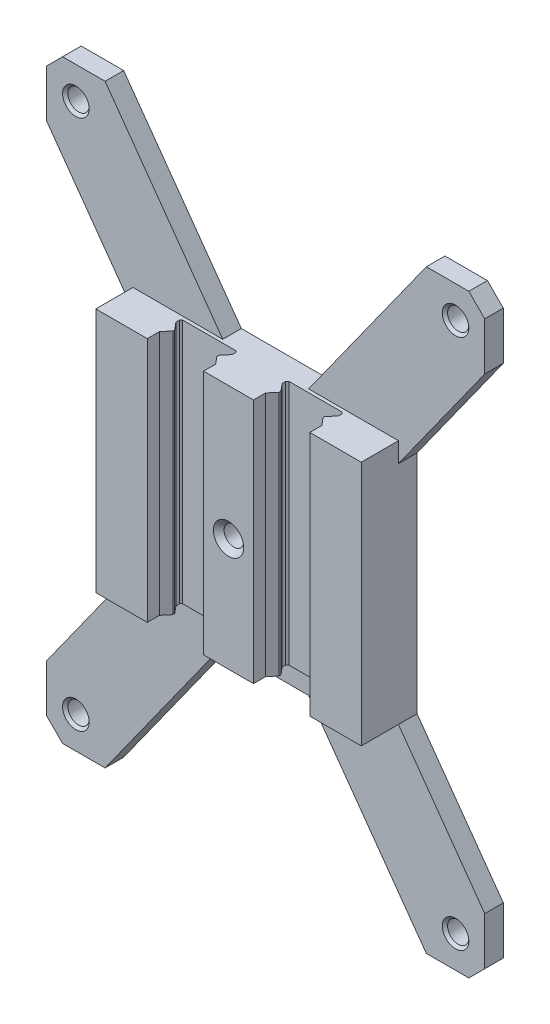
SolidWorks part; units mm, degrees
material "PET"
ref_plane "Přední rovina" through (0, 0, 0) normal (0, 0, 1) x (1, 0, 0)
ref_plane "Horní rovina" through (0, 0, 0) normal (0, 1, 0) x (1, 0, 0)
ref_plane "Pravá rovina" through (0, 0, 0) normal (1, 0, 0) x (0, 0, -1)
sketch "Skica1" plane through (0, 0, 0) normal (0, 0, 1) x (1, 0, 0)
  line L2 (-25, -25) -> (25, -25)
  line L3 (-25, -25) -> (-25, 25)
  line L4 (-25, 25) -> (25, 25)
  line L5 (25, -25) -> (25, 25)
  line L6 (-25, -25) -> (25, 25) construction
  line L7 (-25, 25) -> (25, -25) construction
  point P1 (0, 0)
  dimension "D1" = 50
  dimension "D2" = 50
extrude "Přidat vysunutím1" add sketch "Skica1" along normal blind 10
sketch "Skica3" plane through (0, 25, 0) normal (0, 1, 0) x (1, 0, 0)
  line L0 (-10, 0) -> (-10, -10) construction
  line L1 (25, 0) -> (-25, 0) construction
  line L2 (25, -10) -> (-25, -10) construction
  line L3 (-15, -10) -> (-15, -7.33) construction
  line L4 (-15, -7.33) -> (-13.8337, -5.94) construction
  line L5 (-13.8337, -5.94) -> (-13.8337, -5.39) construction
  line L6 (-13.8337, -5.39) -> (-15, -4) construction
  line L7 (-15, -4) -> (-15, -3.53) construction
  line L8 (-14.8, -3.33) -> (-5.2, -3.33) construction
  line L9 (-5, -10) -> (-5, -7.33) construction
  line L10 (-5, -7.33) -> (-6.1663, -5.94) construction
  line L11 (-6.1663, -5.94) -> (-6.1663, -5.39) construction
  line L12 (-6.1663, -5.39) -> (-5, -4) construction
  line L13 (-5, -4) -> (-5, -3.53) construction
  line L14 (-15, -3.53) -> (-14.8, -3.33) construction
  line L15 (-5.2, -3.33) -> (-5, -3.53) construction
  line L16 (-15.3, -10) -> (-15.3, -7.2208)
  line L17 (-15.3, -7.2208) -> (-14.1337, -5.8308)
  line L18 (-14.1337, -5.8308) -> (-14.1337, -5.4992)
  line L19 (-14.1337, -5.4992) -> (-15.3, -4.1092)
  line L20 (-15.3, -4.1092) -> (-15.3, -3.4305)
  line L21 (-14.9995, -3.13) -> (-5.0005, -3.13)
  line L22 (-15.3, -3.4305) -> (-14.9995, -3.13)
  line L23 (-25, -10) -> (-25, 0) construction
  line L24 (-15.3, -10) -> (-4.7, -10)
  line L25 (-4.7, -3.4305) -> (-5.0005, -3.13)
  line L26 (-4.7, -4.1092) -> (-4.7, -3.4305)
  line L27 (-5.8663, -5.4992) -> (-4.7, -4.1092)
  line L28 (-5.8663, -5.8308) -> (-5.8663, -5.4992)
  line L29 (-4.7, -7.2208) -> (-5.8663, -5.8308)
  line L30 (-4.7, -10) -> (-4.7, -7.2208)
  line L31 (0, 0) -> (0, -10) construction
  line L32 (15.3, -3.4305) -> (14.9995, -3.13)
  line L33 (15.3, -4.1092) -> (15.3, -3.4305)
  line L34 (14.1337, -5.4992) -> (15.3, -4.1092)
  line L35 (14.1337, -5.8308) -> (14.1337, -5.4992)
  line L36 (15.3, -7.2208) -> (14.1337, -5.8308)
  line L37 (15.3, -10) -> (15.3, -7.2208)
  line L38 (15.3, -10) -> (4.7, -10)
  line L39 (4.7, -10) -> (4.7, -7.2208)
  line L40 (4.7, -7.2208) -> (5.8663, -5.8308)
  line L41 (5.8663, -5.8308) -> (5.8663, -5.4992)
  line L42 (5.8663, -5.4992) -> (4.7, -4.1092)
  line L43 (4.7, -4.1092) -> (4.7, -3.4305)
  line L44 (4.7, -3.4305) -> (5.0005, -3.13)
  line L45 (14.9995, -3.13) -> (5.0005, -3.13)
  point P8 (-14.4168, -4.695)
  point P12 (-15, -3.33)
  point P14 (-14.4168, -6.635)
  point P17 (-5.5832, -6.635)
  point P20 (-5.5832, -4.695)
  point P22 (-5, -3.33)
  point P23 (-10, -3.33)
  point P29 (-13.8337, -5.665)
  point P39 (-10, -3.13)
  dimension "D1" = 5
  dimension "D2" = 50
  dimension "D3" = 50
  dimension "D4" = 0.55
  dimension "D5" = 2.67
  dimension "D6" = 3.33
  dimension "D7" = 6.67
  dimension "D8" = 0.3
  dimension "D9" = 0.3
  dimension "D12" = 0.3
  dimension "D13" = 0.3
  dimension "D14" = 0.3
  dimension "D15" = 0.2
  dimension "D16" = 135
  dimension "D17" = 15
extrude "Odebrat vysunutím2" cut sketch "Skica3" against normal through all
sketch "Skica4" plane through (0, 0, 0) normal (0, 0, -1) x (-1, 0, 0)
  line L0 (41.2485, 53.0022) -> (41.2485, 46.0022)
  line L1 (-35.75, -50) -> (35.75, -50) construction
  line L2 (-35.75, -50) -> (-35.75, 50) construction
  line L3 (-35.75, 50) -> (35.75, 50) construction
  line L4 (35.75, -50) -> (35.75, 50) construction
  line L5 (-35.75, -50) -> (35.75, 50) construction
  line L6 (-35.75, 50) -> (35.75, -50) construction
  line L7 (41.2485, 46.0022) -> (34.25, 39) construction
  line L8 (34.25, 39) -> (30.25, 39) construction
  line L9 (30.25, 39) -> (30.25, 56) construction
  line L12 (41.2485, 53.0022) -> (38.25, 56)
  line L13 (38.25, 56) -> (30.25, 56)
  line L14 (35.75, 0) -> (-35.75, 0) construction
  line L15 (38.25, -56) -> (30.25, -56)
  line L16 (41.2485, -53.0022) -> (38.25, -56)
  line L17 (30.25, -39) -> (30.25, -56) construction
  line L18 (34.25, -39) -> (30.25, -39) construction
  line L19 (41.2485, -46.0022) -> (34.25, -39) construction
  line L20 (41.2485, -53.0022) -> (41.2485, -46.0022)
  line L21 (0, 50) -> (0, -50) construction
  line L22 (-41.2485, -53.0022) -> (-41.2485, -46.0022)
  line L23 (-41.2485, -46.0022) -> (-34.25, -39) construction
  line L24 (-34.25, -39) -> (-30.25, -39) construction
  line L25 (-30.25, -39) -> (-30.25, -56) construction
  line L26 (-41.2485, -53.0022) -> (-38.25, -56)
  line L27 (-38.25, -56) -> (-30.25, -56)
  line L28 (25, 21.2727) -> (41.2485, 43.9979)
  line L30 (41.2485, 46.0022) -> (41.2485, 43.9979)
  line L32 (25, -21.2727) -> (41.2485, -43.9979)
  line L33 (41.2485, -46.0022) -> (41.2485, -43.9979)
  line L34 (-41.2485, -46.0022) -> (-41.2485, -43.9979)
  line L35 (-8.085, -25) -> (-30.25, -56)
  line L36 (-25, -21.2727) -> (-41.2485, -43.9979)
  line L37 (8.085, -25) -> (30.25, -56)
  line L38 (-41.2485, 53.0022) -> (-38.25, 56)
  line L39 (-38.25, 56) -> (-30.25, 56)
  line L40 (-41.2485, 46.0022) -> (-41.2485, 43.9979)
  line L41 (-41.2485, 53.0022) -> (-41.2485, 46.0022)
  line L42 (-25, 21.2727) -> (-41.2485, 43.9979)
  line L43 (8.085, 25) -> (30.25, 56)
  line L44 (-8.085, 25) -> (-30.25, 56)
  line L46 (-8.085, 25) -> (8.085, 25)
  line L47 (25, 21.2727) -> (25, -21.2727)
  line L48 (8.085, -25) -> (-8.085, -25)
  line L57 (-25, -21.2727) -> (-25, 21.2727)
  circle A0 centre (35.75, 50) radius 2
  circle A1 centre (35.75, -50) radius 2
  circle A2 centre (-35.75, -50) radius 2
  circle A3 centre (35.75, -50) radius 2
  circle A4 centre (-35.75, -50) radius 2
  circle A5 centre (-35.75, -50) radius 2
  circle A6 centre (-35.75, 50) radius 2
  point P0 (0, 0)
  line M5 (-25, 25) -> (-25, -25)
  line M6 (-25, -25) -> (25, -25)
  line M7 (25, -25) -> (25, 25)
  line M8 (25, 25) -> (-25, 25)
  dimension "D3" = 4
  dimension "D4" = 4
  dimension "D5" = 4
  dimension "D1" = 100
  dimension "D2" = 71.5
  dimension "D6" = 4
  dimension "D7" = 9.9
  dimension "D8" = 7
  dimension "D9" = 4.24
  dimension "D10" = 8
  dimension "D11" = 17
  dimension "D12" = 5.5
  dimension "D13" = 6
extrude "Přidat vysunutím4" add sketch "Skica4" along normal blind 1 and the other way blind 2.5 contours L36 L34 L22 L26 L27 L35 A2 M5 M6 | M8 M5 M6 M7 | L44 L39 L38 L41 L40 L42 A6 M8 M5 | L43 L28 L30 L0 L12 L13 A0 M8 M7 | L37 L15 L16 L20 L33 L32 A1 M6 M7
sketch "Skica6" plane through (0, 0, 10) normal (0, 0, 1) x (1, 0, 0)
  circle A0 centre (0, 0) radius 1.85
  dimension "D1" = 3.7
extrude "Odebrat vysunutím3" cut sketch "Skica6" against normal through all
sketch "Skica7" plane through (0, 25, 0) normal (0, 1, 0) x (1, 0, 0)
  line L0 (25, -10) -> (25, -2.5) construction
  line L1 (-25, -10) -> (25, -10)
  line L2 (-25, -10) -> (-25, -9)
  line L3 (-25, -9) -> (25, -9)
  line L4 (25, -10) -> (25, -9)
  line L5 (-25, -10) -> (25, -9) construction
  line L6 (-25, -9) -> (25, -10) construction
  point P4 (0, -9.5)
  dimension "D1" = 1
extrude "Odebrat vysunutím4" cut sketch "Skica7" against normal through all
sketch "Skica9" plane through (25, 0, 0) normal (1, 0, 0) x (0, 0, -1)
  line L1 (-9, -25) -> (-2.5, -25)
  line L2 (-9, -25) -> (-9, -21.2727)
  line L3 (-9, -21.2727) -> (-2.5, -21.2727)
  line L4 (-2.5, -25) -> (-2.5, -21.2727)
  line L5 (-9, -25) -> (-2.5, -21.2727) construction
  line L6 (-9, -21.2727) -> (-2.5, -25) construction
  point P4 (-5.75, -23.1364)
extrude "Odebrat vysunutím6" cut sketch "Skica9" against normal through all
chamfer "Zkosení2" distance 0.5 angle 45 4 edges at (33.75, 50, 2.5) (-37.75, 50, 2.5) (-37.75, -50, 2.5) (33.75, -50, 2.5)
sketch "Skica10" plane through (0, 0, 9) normal (0, 0, 1) x (1, 0, 0)
  line L4 (-4.7, 25) -> (-4.7, -21.2727)
  line L5 (-4.7, -21.2727) -> (4.7, -21.2727)
  line L6 (4.7, -21.2727) -> (4.7, 25)
  line L7 (4.7, 25) -> (-4.7, 25)
  line L8 (-4.7, 25) -> (-4.7, -21.2727)
  line L9 (-4.7, -21.2727) -> (4.7, -21.2727)
  line L10 (4.7, -21.2727) -> (4.7, 25)
  line L11 (4.7, 25) -> (-4.7, 25)
  line L12 (-25, 25) -> (-25, -21.2727)
  line L13 (-25, -21.2727) -> (-15.3, -21.2727)
  line L14 (-15.3, -21.2727) -> (-15.3, 25)
  line L15 (-15.3, 25) -> (-25, 25)
  line L16 (-25, 25) -> (-25, -21.2727)
  line L17 (-25, -21.2727) -> (-15.3, -21.2727)
  line L18 (-15.3, -21.2727) -> (-15.3, 25)
  line L19 (-15.3, 25) -> (-25, 25)
  line L20 (15.3, 25) -> (15.3, -21.2727)
  line L21 (15.3, -21.2727) -> (25, -21.2727)
  line L22 (25, -21.2727) -> (25, 25)
  line L23 (25, 25) -> (15.3, 25)
  line L24 (15.3, 25) -> (15.3, -21.2727)
  line L25 (15.3, -21.2727) -> (25, -21.2727)
  line L26 (25, -21.2727) -> (25, 25)
  line L27 (25, 25) -> (15.3, 25)
  circle A0 centre (0, 0) radius 1.85 construction
  circle A1 centre (0, 0) radius 1.85
  dimension "D1" = 0
  dimension "D2" = 0
  dimension "D3" = 0
extrude "Přidat vysunutím5" add sketch "Skica10" along normal blind 0.5
chamfer "Zkosení3" distance 1 angle 45 1 edges at (1.85, 0, 9.5)
